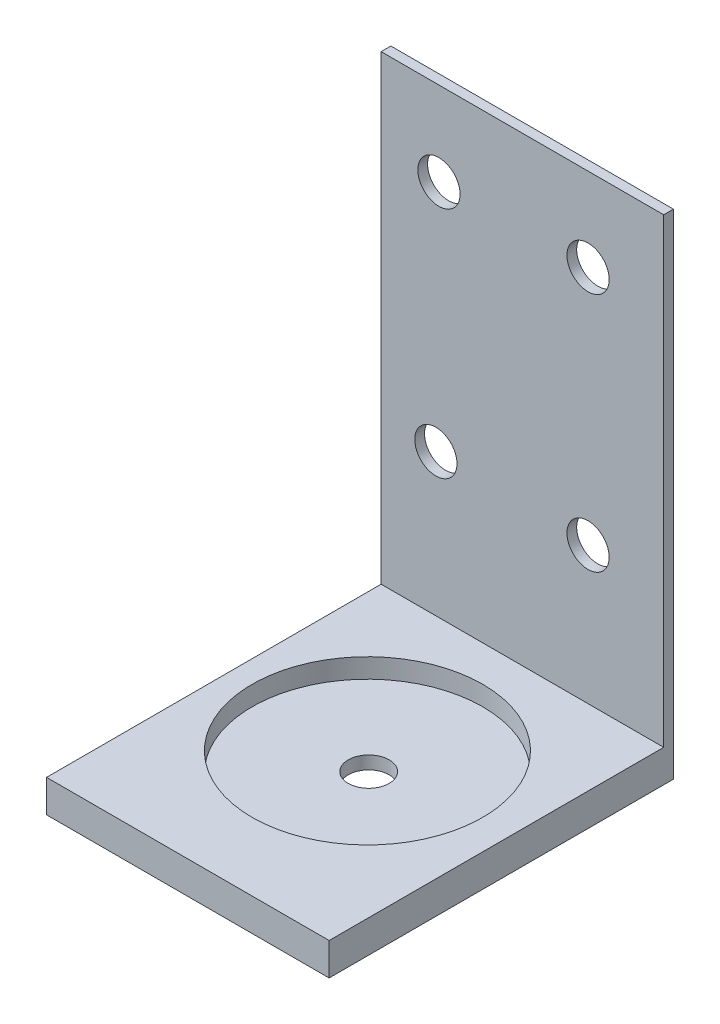
SolidWorks part; units mm, degrees
ref_plane "Front Plane" through (0, 0, 0) normal (0, 0, 1) x (1, 0, 0)
ref_plane "Top Plane" through (0, 0, 0) normal (0, 1, 0) x (1, 0, 0)
ref_plane "Right Plane" through (0, 0, 0) normal (1, 0, 0) x (0, 0, -1)
sketch "Sketch1" plane through (0, 0, 0) normal (0, 1, 0) x (1, 0, 0)
  line L1 (-12.6914, -6.8417) -> (9.4066, -6.8417)
  line L2 (-12.6914, -6.8417) -> (-12.6914, 20.0823)
  line L3 (-12.6914, 20.0823) -> (9.4066, 20.0823)
  line L4 (9.4066, -6.8417) -> (9.4066, 20.0823)
  dimension "D1" = 22.098
  dimension "D2" = 26.924
extrude "Boss-Extrude1" add sketch "Sketch1" along normal blind 2.54
sketch "Sketch2" plane through (0, 2.54, 0) normal (0, 1, 0) x (1, 0, 0)
  line L0 (9.4066, -6.8417) -> (9.4066, 20.0823) construction
  line L1 (-12.6914, 20.0823) -> (9.4066, 20.0823)
  line L2 (-12.6914, 20.0823) -> (-12.6914, 19.3203)
  line L3 (-12.6914, 19.3203) -> (9.4066, 19.3203)
  line L4 (9.4066, 20.0823) -> (9.4066, 19.3203)
  dimension "D1" = 0.762
  dimension "D2" = 22.098
extrude "Boss-Extrude2" add sketch "Sketch2" along normal blind 36.068
sketch "Sketch3" plane through (0, 2.54, 0) normal (0, 1, 0) x (1, 0, 0)
  circle A0 centre (-1.9413, 7.5003) radius 9.017
  dimension "D1" = 18.034
sketch "Sketch4" plane through (0, 0, -19.3203) normal (0, 0, 1) x (1, 0, 0)
  circle A0 centre (-8.1681, 32.0396) radius 1.651
  dimension "D1" = 3.302
extrude "Cut-Extrude1" cut sketch "Sketch4" against normal blind 0.762
extrude "Cut-Extrude2" cut sketch "Sketch3" against normal blind 1.524
sketch "Sketch5" plane through (0, 1.016, 0) normal (0, 1, 0) x (1, 0, 0)
  circle A0 centre (-2.0077, 7.6663) radius 1.5995
extrude "Cut-Extrude3" cut sketch "Sketch5" against normal blind 1.27
sketch "Sketch6" plane through (0, 0, -19.3203) normal (0, 0, 1) x (1, 0, 0)
  circle A0 centre (3.4918, 32.0875) radius 1.651
  circle A1 centre (-8.4081, 13.662) radius 1.651
  circle A2 centre (3.4918, 13.2781) radius 1.651
  dimension "D1" = 3.302
  dimension "D2" = 3.302
  dimension "D3" = 3.302
extrude "Cut-Extrude4" cut sketch "Sketch6" against normal blind 0.762
equation "\"H1\"= 22mm"
equation "\"L1\"= 36mm"
equation "\"T1\" = 0.68mm"
equation "\"H2\"= 27mm"
equation "\"L2\"= 22mm"
equation "\"T2\"= 2.59mm"
equation "\"Sc\"= 3.4mm"
equation "\"Mount\"= 18mm"
